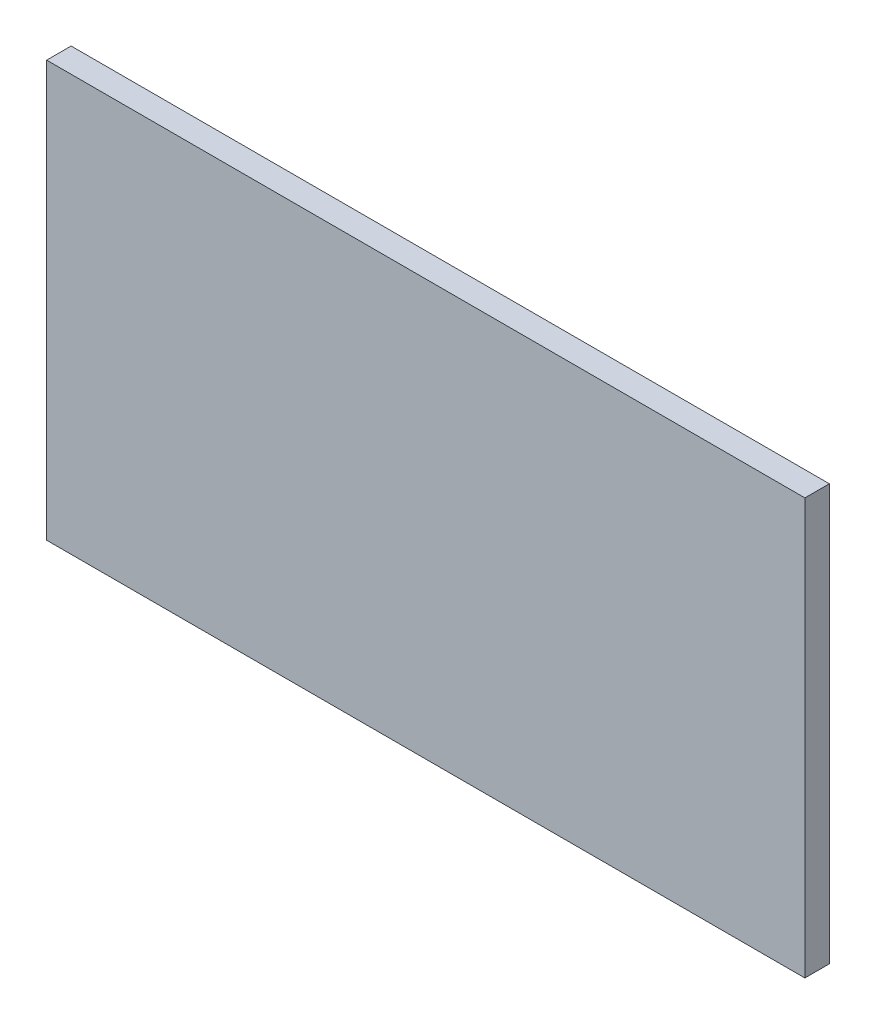
SolidWorks part; units mm, degrees
ref_plane "Front Plane" through (0, 0, 0) normal (0, 0, 1) x (1, 0, 0)
ref_plane "Top Plane" through (0, 0, 0) normal (0, 1, 0) x (1, 0, 0)
ref_plane "Right Plane" through (0, 0, 0) normal (1, 0, 0) x (0, 0, -1)
sketch "Sketch1" plane through (0, 0, 0) normal (0, 0, 1) x (1, 0, 0)
  line L1 (114.3, -6.35) -> (-82.55, -6.35)
  line L2 (114.3, -6.35) -> (114.3, 101.6)
  line L3 (114.3, 101.6) -> (-82.55, 101.6)
  line L4 (-82.55, -6.35) -> (-82.55, 101.6)
extrude "Boss-Extrude1" add sketch "Sketch1" along normal blind 6.35
